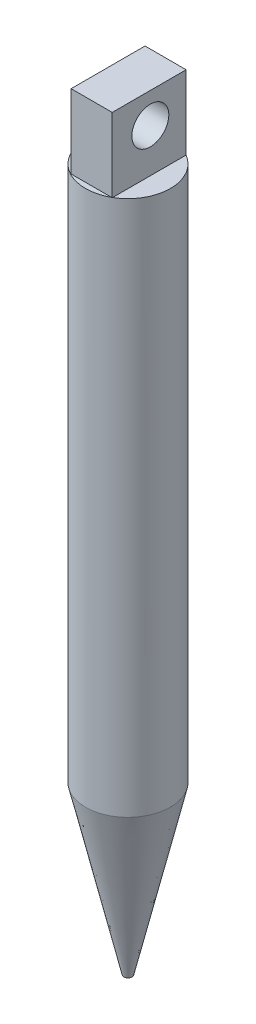
SolidWorks part; units mm, degrees
material "PF"
ref_plane "Plan de face" through (0, 0, 0) normal (0, 0, 1) x (1, 0, 0)
ref_plane "Plan de dessus" through (0, 0, 0) normal (0, 1, 0) x (1, 0, 0)
ref_plane "Plan de droite" through (0, 0, 0) normal (1, 0, 0) x (0, 0, -1)
sketch "Esquisse1" plane through (0, 0, 0) normal (0, 0, 1) x (1, 0, 0)
  line L1 (-2.1374, 2.6997) -> (2.3126, 2.6997)
  line L2 (-2.1374, 2.6997) -> (-2.1374, -5.3003)
  line L3 (-2.1374, -5.3003) -> (2.3126, -5.3003)
  line L4 (2.3126, 2.6997) -> (2.3126, -5.3003)
  dimension "D1" = 4.45
  dimension "D2" = 8
extrude "Boss.-Extru.1" add sketch "Esquisse1" along normal blind 8
sketch "Esquisse2" plane through (0, -5.3003, 0) normal (0, -1, 0) x (1, 0, 0)
  circle A0 centre (0, 3.9834) radius 4.5979
extrude "Boss.-Extru.2" add sketch "Esquisse2" along normal blind 58
sketch "Esquisse4" plane through (2.3126, 0, 0) normal (1, 0, 0) x (0, 0, -1)
  circle A0 centre (-3.8757, -0.5893) radius 2
extrude "Enlèv. mat.-Extru.1" cut sketch "Esquisse4" against normal blind 18
sketch "Esquisse5" plane through (0, -63.3003, 0) normal (0, -1, 0) x (1, 0, 0)
  circle A0 centre (0, 3.9834) radius 4.5979
extrude "Boss.-Extru.3" add sketch "Esquisse5" along normal blind 18 draft 13
